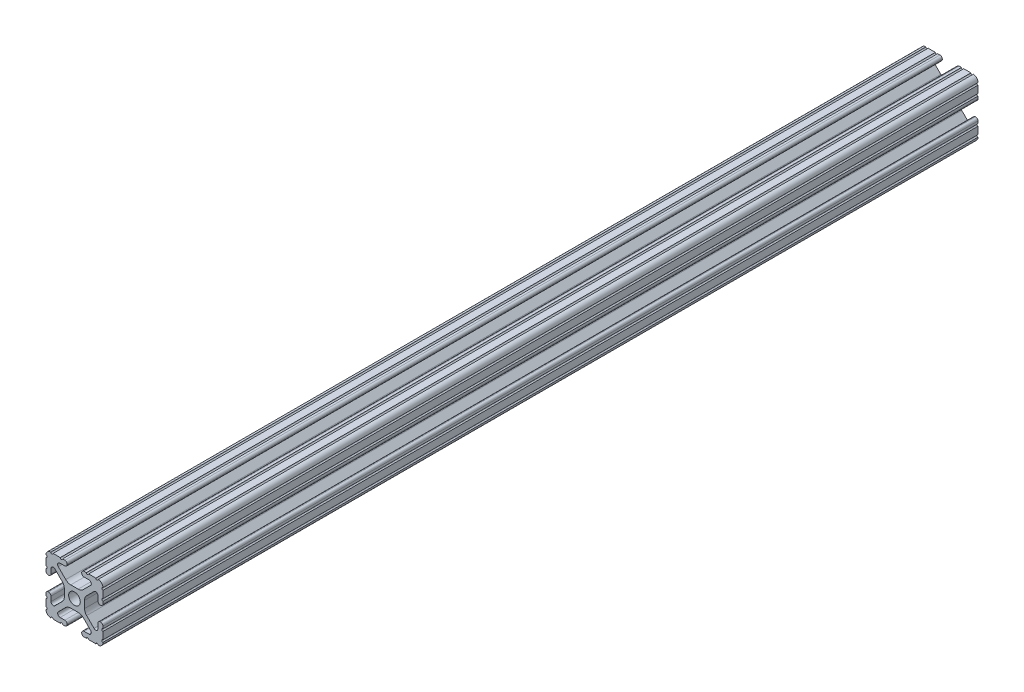
SolidWorks part; units mm, degrees
ref_plane "Front Plane" through (0, 0, 0) normal (0, 0, 1) x (1, 0, 0)
ref_plane "Top Plane" through (0, 0, 0) normal (0, 1, 0) x (1, 0, 0)
ref_plane "Right Plane" through (0, 0, 0) normal (1, 0, 0) x (0, 0, -1)
sketch "Sketch1" plane through (0, 0, 0) normal (0, 0, 1) x (1, 0, 0)
  line L88 (-7.1797, -8.6452) -> (-3.9523, -5.4237)
  line L89 (-1.7093, -4.4958) -> (1.7093, -4.4958)
  line L90 (3.9523, -5.4237) -> (7.1797, -8.6452)
  line L91 (6.4164, -10.4902) -> (4.2875, -10.4902)
  line L92 (3.2385, -11.5392) -> (3.2385, -11.651)
  line L93 (4.2875, -12.7) -> (5.3171, -12.7)
  line L94 (6.3331, -12.7) -> (9.5504, -12.7)
  line L95 (12.7, -9.5504) -> (12.7, -6.3331)
  line L96 (12.7, -5.3171) -> (12.7, -4.2875)
  line L97 (11.651, -3.2385) -> (11.5392, -3.2385)
  line L98 (10.4902, -4.2875) -> (10.4902, -6.4021)
  line L99 (8.7371, -7.1294) -> (5.441, -3.8408)
  line L100 (4.5085, -1.5932) -> (4.5085, 1.5932)
  line L101 (5.441, 3.8408) -> (8.7371, 7.1294)
  line L102 (10.4902, 6.4021) -> (10.4902, 4.2875)
  line L103 (11.5392, 3.2385) -> (11.651, 3.2385)
  line L104 (12.7, 4.2875) -> (12.7, 5.3171)
  line L105 (12.7, 6.3331) -> (12.7, 9.5504)
  line L106 (9.5504, 12.7) -> (6.3331, 12.7)
  line L107 (5.3171, 12.7) -> (4.2875, 12.7)
  line L108 (3.2385, 11.651) -> (3.2385, 11.5392)
  line L109 (4.2875, 10.4902) -> (6.4768, 10.4902)
  line L110 (7.207, 8.7244) -> (3.8983, 5.4232)
  line L111 (1.6558, 4.4958) -> (-1.6558, 4.4958)
  line L112 (-3.8983, 5.4232) -> (-7.207, 8.7244)
  line L113 (-6.4768, 10.4902) -> (-4.2875, 10.4902)
  line L114 (-3.2385, 11.5392) -> (-3.2385, 11.651)
  line L115 (-4.2875, 12.7) -> (-5.3171, 12.7)
  line L116 (-6.3331, 12.7) -> (-9.5504, 12.7)
  line L117 (-12.7, 9.5504) -> (-12.7, 6.3331)
  line L118 (-12.7, 5.3171) -> (-12.7, 4.2875)
  line L119 (-11.651, 3.2385) -> (-11.5392, 3.2385)
  line L120 (-10.4902, 4.2875) -> (-10.4902, 6.4021)
  line L121 (-8.7371, 7.1294) -> (-5.441, 3.8408)
  line L122 (-4.5085, 1.5932) -> (-4.5085, -1.5932)
  line L123 (-5.441, -3.8408) -> (-8.7371, -7.1294)
  line L124 (-10.4902, -6.4021) -> (-10.4902, -4.2875)
  line L125 (-11.5392, -3.2385) -> (-11.651, -3.2385)
  line L126 (-12.7, -4.2875) -> (-12.7, -5.3171)
  line L127 (-12.7, -6.3331) -> (-12.7, -9.5504)
  line L128 (-9.5504, -12.7) -> (-6.3331, -12.7)
  line L129 (-5.3171, -12.7) -> (-4.2875, -12.7)
  line L130 (-3.2385, -11.651) -> (-3.2385, -11.5392)
  line L131 (-4.2875, -10.4902) -> (-6.4164, -10.4902)
  circle A1 centre (0, 0) radius 2.6035
  arc A104 (-7.1797, -8.6452) -> (-6.4164, -10.4902) centre (-6.4164, -9.4098) ccw
  arc A105 (-1.7093, -4.4958) -> (-3.9523, -5.4237) centre (-1.7093, -7.6708) ccw
  arc A106 (3.9523, -5.4237) -> (1.7093, -4.4958) centre (1.7093, -7.6708) ccw
  arc A107 (6.4164, -10.4902) -> (7.1797, -8.6452) centre (6.4164, -9.4098) ccw
  arc A108 (4.2875, -10.4902) -> (3.2385, -11.5392) centre (4.2875, -11.5392) ccw
  arc A109 (3.2385, -11.651) -> (4.2875, -12.7) centre (4.2875, -11.651) ccw
  arc A110 (6.3331, -12.7) -> (5.3171, -12.7) centre (5.8251, -12.7) ccw
  arc A111 (10.5664, -12.6998) -> (9.5504, -12.7) centre (10.0584, -12.7) ccw
  arc A112 (10.5664, -12.6998) -> (12.6998, -10.5664) centre (10.5918, -10.5918) ccw
  arc A113 (12.7, -9.5504) -> (12.6998, -10.5664) centre (12.7, -10.0584) ccw
  arc A114 (12.7, -5.3171) -> (12.7, -6.3331) centre (12.7, -5.8251) ccw
  arc A115 (12.7, -4.2875) -> (11.651, -3.2385) centre (11.651, -4.2875) ccw
  arc A116 (11.5392, -3.2385) -> (10.4902, -4.2875) centre (11.5392, -4.2875) ccw
  arc A117 (8.7371, -7.1294) -> (10.4902, -6.4021) centre (9.4628, -6.4021) ccw
  arc A118 (4.5085, -1.5932) -> (5.441, -3.8408) centre (7.6835, -1.5932) ccw
  arc A119 (5.441, 3.8408) -> (4.5085, 1.5932) centre (7.6835, 1.5932) ccw
  arc A120 (10.4902, 6.4021) -> (8.7371, 7.1294) centre (9.4628, 6.4021) ccw
  arc A121 (10.4902, 4.2875) -> (11.5392, 3.2385) centre (11.5392, 4.2875) ccw
  arc A122 (11.651, 3.2385) -> (12.7, 4.2875) centre (11.651, 4.2875) ccw
  arc A123 (12.7, 6.3331) -> (12.7, 5.3171) centre (12.7, 5.8251) ccw
  arc A124 (12.6998, 10.5664) -> (12.7, 9.5504) centre (12.7, 10.0584) ccw
  arc A125 (12.6998, 10.5664) -> (10.5664, 12.6998) centre (10.5918, 10.5918) ccw
  arc A126 (9.5504, 12.7) -> (10.5664, 12.6998) centre (10.0584, 12.7) ccw
  arc A127 (5.3171, 12.7) -> (6.3331, 12.7) centre (5.8251, 12.7) ccw
  arc A128 (4.2875, 12.7) -> (3.2385, 11.651) centre (4.2875, 11.651) ccw
  arc A129 (3.2385, 11.5392) -> (4.2875, 10.4902) centre (4.2875, 11.5392) ccw
  arc A130 (7.207, 8.7244) -> (6.4768, 10.4902) centre (6.4768, 9.4563) ccw
  arc A131 (1.6558, 4.4958) -> (3.8983, 5.4232) centre (1.6558, 7.6708) ccw
  arc A132 (-3.8983, 5.4232) -> (-1.6558, 4.4958) centre (-1.6558, 7.6708) ccw
  arc A133 (-6.4768, 10.4902) -> (-7.207, 8.7244) centre (-6.4768, 9.4563) ccw
  arc A134 (-4.2875, 10.4902) -> (-3.2385, 11.5392) centre (-4.2875, 11.5392) ccw
  arc A135 (-3.2385, 11.651) -> (-4.2875, 12.7) centre (-4.2875, 11.651) ccw
  arc A136 (-6.3331, 12.7) -> (-5.3171, 12.7) centre (-5.8251, 12.7) ccw
  arc A137 (-10.5664, 12.6998) -> (-9.5504, 12.7) centre (-10.0584, 12.7) ccw
  arc A138 (-10.5664, 12.6998) -> (-12.6998, 10.5664) centre (-10.5918, 10.5918) ccw
  arc A139 (-12.7, 9.5504) -> (-12.6998, 10.5664) centre (-12.7, 10.0584) ccw
  arc A140 (-12.7, 5.3171) -> (-12.7, 6.3331) centre (-12.7, 5.8251) ccw
  arc A141 (-12.7, 4.2875) -> (-11.651, 3.2385) centre (-11.651, 4.2875) ccw
  arc A142 (-11.5392, 3.2385) -> (-10.4902, 4.2875) centre (-11.5392, 4.2875) ccw
  arc A143 (-8.7371, 7.1294) -> (-10.4902, 6.4021) centre (-9.4628, 6.4021) ccw
  arc A144 (-4.5085, 1.5932) -> (-5.441, 3.8408) centre (-7.6835, 1.5932) ccw
  arc A145 (-5.441, -3.8408) -> (-4.5085, -1.5932) centre (-7.6835, -1.5932) ccw
  arc A146 (-10.4902, -6.4021) -> (-8.7371, -7.1294) centre (-9.4628, -6.4021) ccw
  arc A147 (-10.4902, -4.2875) -> (-11.5392, -3.2385) centre (-11.5392, -4.2875) ccw
  arc A148 (-11.651, -3.2385) -> (-12.7, -4.2875) centre (-11.651, -4.2875) ccw
  arc A149 (-12.7, -6.3331) -> (-12.7, -5.3171) centre (-12.7, -5.8251) ccw
  arc A150 (-12.6998, -10.5664) -> (-12.7, -9.5504) centre (-12.7, -10.0584) ccw
  arc A151 (-12.6998, -10.5664) -> (-10.5664, -12.6998) centre (-10.5918, -10.5918) ccw
  arc A152 (-9.5504, -12.7) -> (-10.5664, -12.6998) centre (-10.0584, -12.7) ccw
  arc A153 (-5.3171, -12.7) -> (-6.3331, -12.7) centre (-5.8251, -12.7) ccw
  arc A154 (-4.2875, -12.7) -> (-3.2385, -11.651) centre (-4.2875, -11.651) ccw
  arc A155 (-3.2385, -11.5392) -> (-4.2875, -10.4902) centre (-4.2875, -11.5392) ccw
extrude "Boss-Extrude1" add sketch "Sketch1" along normal mid plane 609.6
sketch "Sketch5" plane through (0, 0, 304.8) normal (0, 0, 1) x (1, 0, 0)
  line L1 (-33.2223, 36.1775) -> (46.6003, 36.1775)
  line L2 (-33.2223, 36.1775) -> (-33.2223, -44.4182)
  line L3 (-33.2223, -44.4182) -> (46.6003, -44.4182)
  line L4 (46.6003, 36.1775) -> (46.6003, -44.4182)
extrude "Cut-Extrude4" cut sketch "Sketch5" against normal blind 219.075
